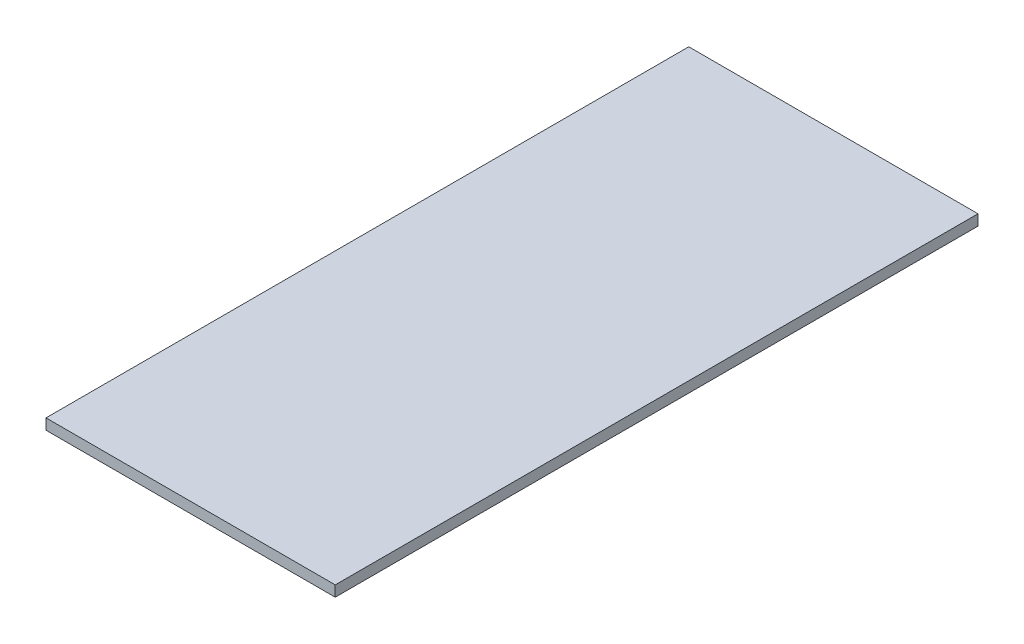
SolidWorks part; units mm, degrees
ref_plane "정면" through (0, 0, 0) normal (0, 0, 1) x (1, 0, 0)
ref_plane "윗면" through (0, 0, 0) normal (0, 1, 0) x (1, 0, 0)
ref_plane "우측면" through (0, 0, 0) normal (1, 0, 0) x (0, 0, -1)
sketch "스케치1" plane through (0, 0, 0) normal (0, 1, 0) x (1, 0, 0)
  line L1 (-40.5, 90) -> (40.5, 90)
  line L2 (-40.5, 90) -> (-40.5, -90)
  line L3 (-40.5, -90) -> (40.5, -90)
  line L4 (40.5, 90) -> (40.5, -90)
  line L5 (-40.5, 90) -> (40.5, -90) construction
  line L6 (-40.5, -90) -> (40.5, 90) construction
  point P0 (0, 0)
  dimension "D1" = 81
  dimension "D2" = 180
extrude "보스-돌출1" add sketch "스케치1" along normal blind 3
